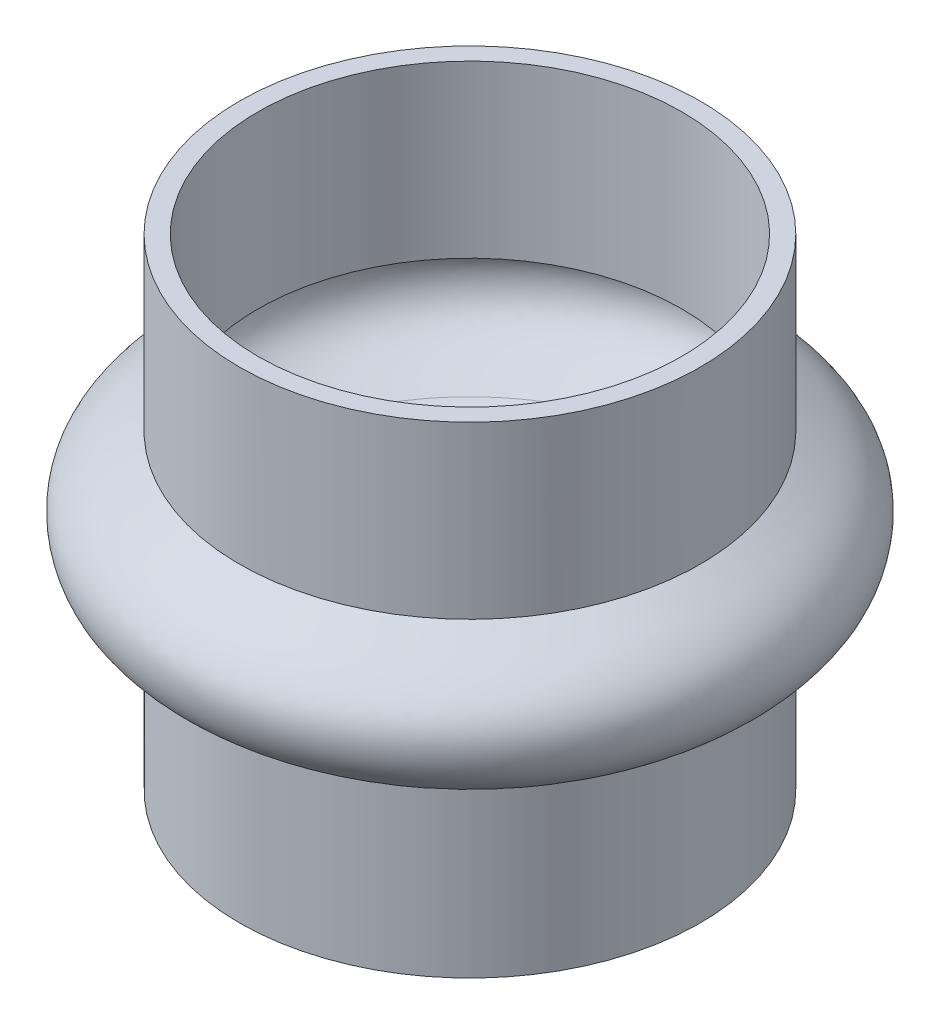
SolidWorks part; units mm, degrees
ref_plane "Front Plane" through (0, 0, 0) normal (0, 0, 1) x (1, 0, 0)
ref_plane "Top Plane" through (0, 0, 0) normal (0, 1, 0) x (1, 0, 0)
ref_plane "Right Plane" through (0, 0, 0) normal (1, 0, 0) x (0, 0, -1)
sketch "Sketch1" plane through (0, 0, 0) normal (0, 0, 1) x (1, 0, 0)
  line L0 (-921.4581, 1439.0368) -> (211.8752, 1439.0368) construction
  line L1 (-99.3333, 446.5) -> (103.3333, 446.5) construction
  line L2 (3.2388, 58.9758) -> (39.625, 58.9758) construction
  line L3 (20.8253, 76.5393) -> (20.8253, 40.3207) construction
  line L4 (7.3253, 63.4119) -> (20.8253, 63.4119) construction
  line L5 (7.3253, 63.4119) -> (20.8253, 76.5393) construction
  line L6 (7.3253, 63.4119) -> (8.411, 63.4119)
  line L7 (8.411, 63.4119) -> (7.5555, 62.9681)
  line L8 (7.3735, 55.6488) -> (8.166, 55.2112)
  line L9 (8.166, 55.2112) -> (7.1318, 55.2112)
  spline S0 degree 3 poles (7.3253, 63.4119) (6.0111, 62.7301) (2.9718, 61.4252) (3.4634, 56.9126) (5.9426, 55.8679) (7.1318, 55.2112) knots 0 0 0 0 0.43 0.624673 1 1 1 1
  spline S1 degree 1 poles (7.5555, 62.9681) (7.3735, 55.6488) knots 0 0 1 1 construction
  spline S2 degree 3 poles (7.5555, 62.9681) (7.35, 62.8614) (6.9471, 62.6604) (6.0541, 62.2018) (4.9545, 61.5406) (4.1595, 60.7257) (3.8436, 60.0138) (3.7346, 59.1782) (3.99, 58.0647) (4.8318, 57.1066) (6.086, 56.3114) (6.9493, 55.8831) (7.3735, 55.6488) knots 0 0 0 0 0.0625 0.125 0.25 0.375 0.4375 0.5 0.625 0.75 0.875 1 1 1 1
  dimension "D1" = 36.3862
  dimension "D2" = 0.5
  dimension "D3" = 13.5
revolve "Revolve1" add sketch "Sketch1" angle 360 about L3
ref_plane "Plane1" through (0, 59.3115, 0) normal (0, 1, 0) x (1, 0, 0)
sketch "Sketch2" plane through (0, 63.4119, 0) normal (0, 1, 0) x (1, 0, 0)
  circle A0 centre (20.8253, 0) radius 13.5
  circle A1 centre (20.8253, 0) radius 13.5 construction
  circle A2 centre (20.8253, 0) radius 12.4143
  circle A3 centre (20.8253, 0) radius 12.4143 construction
extrude "Boss-Extrude1" add sketch "Sketch2" along normal blind 10
mirror "Mirror1" about plane through (0, 59.3115, 0) normal (0, 1, 0) of "Boss-Extrude1"
